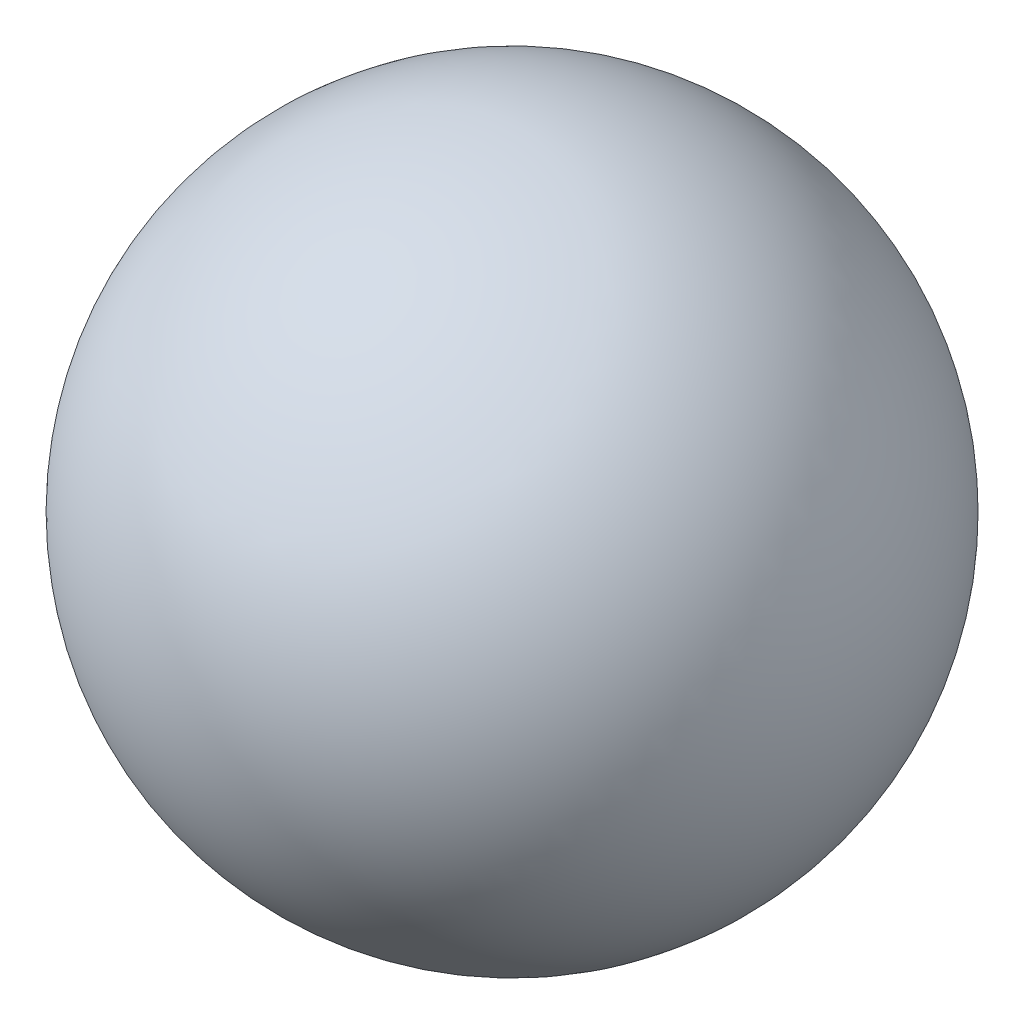
SolidWorks part; units mm, degrees
ref_plane "Front Plane" through (0, 0, 0) normal (0, 0, 1) x (1, 0, 0)
ref_plane "Top Plane" through (0, 0, 0) normal (0, 1, 0) x (1, 0, 0)
ref_plane "Right Plane" through (0, 0, 0) normal (1, 0, 0) x (0, 0, -1)
sketch "Sketch1" plane through (0, 0, 0) normal (0, 0, 1) x (1, 0, 0)
  line L2 (-333.8509, 56.0965) -> (-337.0357, 62.33)
  arc A2 (-337.0357, 62.33) -> (-333.8509, 56.0965) centre (-335.4433, 59.2132) ccw
revolve "Revolve1" add sketch "Sketch1" angle 360 about L2
